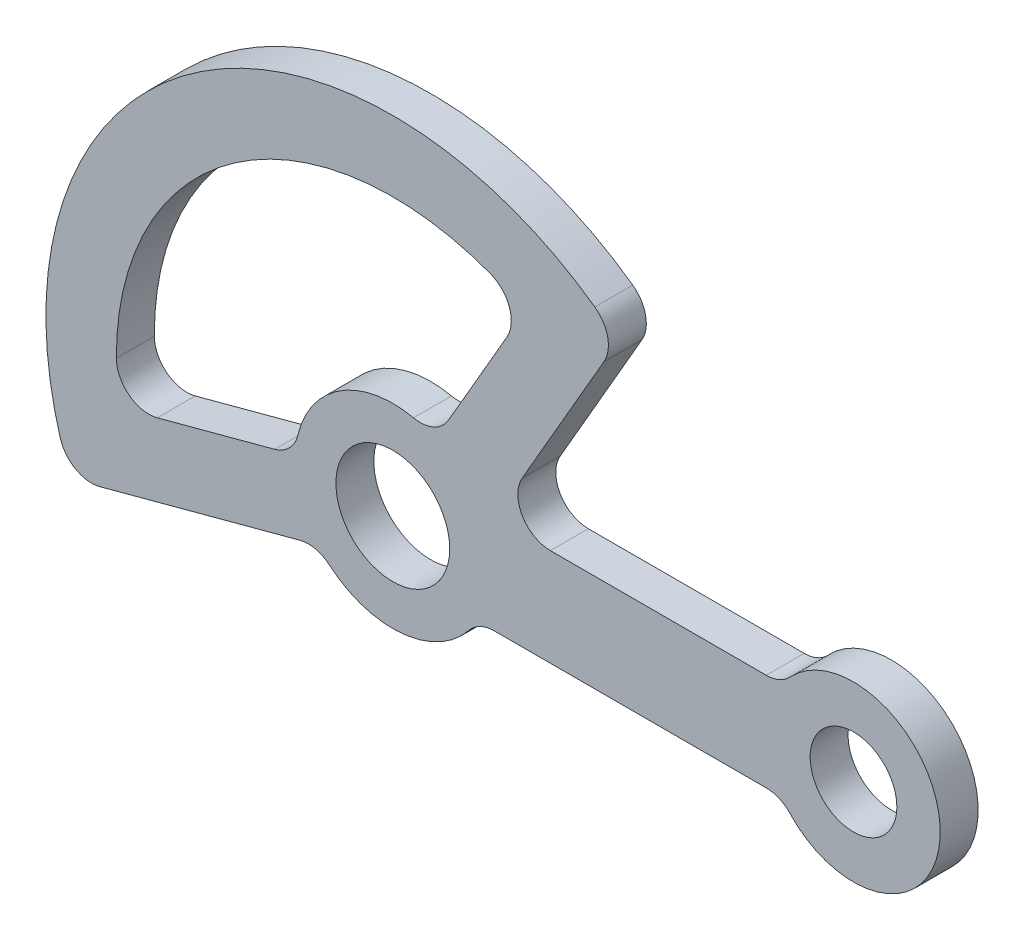
SolidWorks part; units mm, degrees
ref_plane "Płaszczyzna przednia" through (0, 0, 0) normal (0, 0, 1) x (1, 0, 0)
ref_plane "Płaszczyzna górna" through (0, 0, 0) normal (0, 1, 0) x (1, 0, 0)
ref_plane "Płaszczyzna prawa" through (0, 0, 0) normal (1, 0, 0) x (0, 0, -1)
sketch "Szkic1" plane through (0, 0, 0) normal (0, 0, 1) x (1, 0, 0)
  line L0 (0, 0) -> (85, 0) construction
  line L1 (29.0715, 9) -> (68.9065, 9)
  line L2 (23.8754, 18) -> (38.9731, 44.15)
  line L3 (0, 0) -> (0, 76.4741) construction
  line L4 (18.735, -9) -> (68.9065, -9)
  line L5 (-54.037, -22.3412) -> (-17.1393, -12.4545)
  line L6 (10.2817, 20.455) -> (21.054, 39.1133)
  line L7 (0, 0) -> (-87.0658, 0) construction
  line L8 (-43.4464, -6.0449) -> (-21.7961, -0.2437)
  circle A0 centre (0, 0) radius 10.5
  circle A1 centre (85, 0) radius 8
  circle A2 centre (0, 0) radius 18
  circle A3 centre (85, 0) radius 16
  arc A4 (68.9065, 9) -> (73.2957, 10.9091) centre (68.9065, 15) ccw
  arc A5 (29.0715, 9) -> (23.8754, 18) centre (29.0715, 15) cw
  arc A6 (38.9731, 44.15) -> (37.2711, 52.0276) centre (33.7769, 47.15) ccw
  arc A7 (37.2711, 52.0276) -> (-61.3406, -18.2573) centre (0, 0) ccw
  arc A8 (-61.3406, -18.2573) -> (-54.037, -22.3412) centre (-55.5899, -16.5457) ccw
  arc A9 (68.9065, -9) -> (73.2957, -10.9091) centre (68.9065, -15) cw
  arc A10 (-17.1393, -12.4545) -> (-11.6898, -13.6876) centre (-15.5864, -18.2501) cw
  arc A11 (18.735, -9) -> (14.0512, -11.25) centre (18.735, -15) ccw
  arc A12 (-43.4464, -6.0449) -> (-50.9992, -0.2826) centre (-44.9993, -0.2493) cw
  arc A13 (21.054, 39.1133) -> (17.9722, 47.7284) centre (15.8579, 42.1133) ccw
  arc A14 (-50.9992, -0.2826) -> (17.9722, 47.7284) centre (0, 0) cw
  arc A15 (-21.7961, -0.2437) -> (-17.5118, 4.1639) centre (-23.349, 5.5518) ccw
  arc A16 (10.2817, 20.455) -> (3.8141, 17.5913) centre (5.0855, 23.455) cw
  dimension "D1" = 21
  dimension "D2" = 16
  dimension "D3" = 32
  dimension "D5" = 36
  dimension "D6" = 6
  dimension "D7" = 6
  dimension "D9" = 64
  dimension "D14" = 51
  dimension "D15" = 6
  dimension "D16" = 6
  dimension "D17" = 6
  dimension "D18" = 6
  dimension "D19" = 6
  dimension "D21" = 6
  dimension "D22" = 6
  dimension "D23" = 6
  dimension "D24" = 6
  dimension "D4" = 85
  dimension "D8" = 18
  dimension "D10" = 13
  dimension "D11" = 30
  dimension "D12" = 13
  dimension "D13" = 15
  dimension "D20" = 38.1993
  dimension "D25" = 30.1954
extrude "Dodanie-wyciągnięcie1" add sketch "Szkic1" along normal blind 7 contours L6 A16 A2 A11 L4 A9 A3 A4 L1 A5 L2 A6 A7 A8 L5 A10 A15 L8 A12 A14 A13 | A2 A0 | A3 A1
